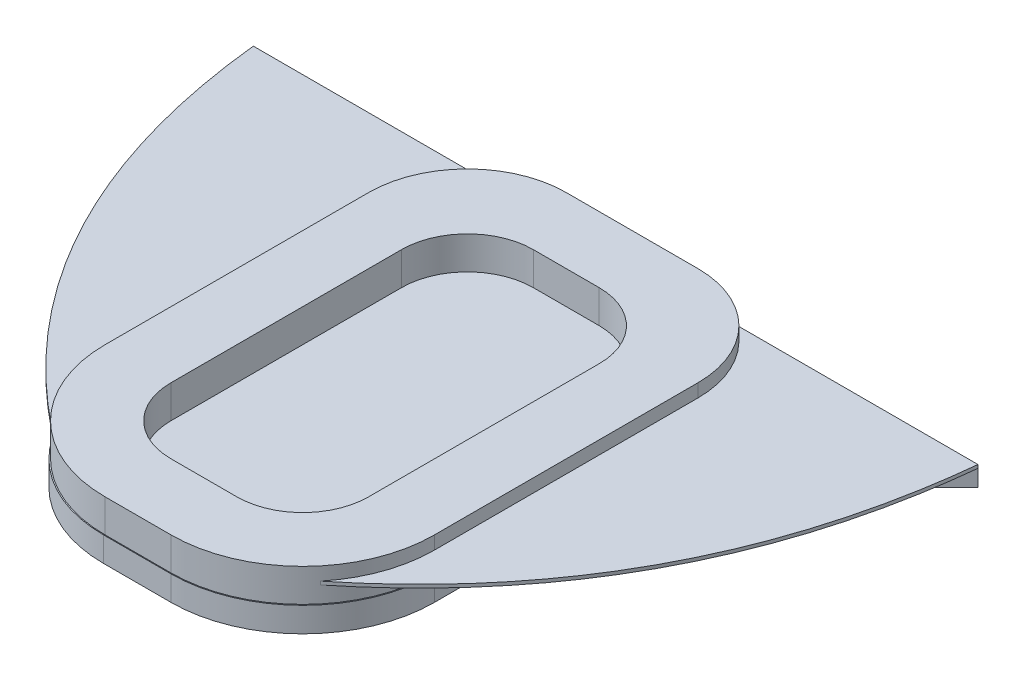
SolidWorks part; units mm, degrees
ref_plane "前视基准面" through (0, 0, 0) normal (0, 0, 1) x (1, 0, 0)
ref_plane "上视基准面" through (0, 0, 0) normal (0, 1, 0) x (1, 0, 0)
ref_plane "右视基准面" through (0, 0, 0) normal (1, 0, 0) x (0, 0, -1)
sketch "草图1" plane through (0, 0, 0) normal (0, 1, 0) x (1, 0, 0)
  line L1 (-4.05, 15.05) -> (4.05, 15.05)
  line L2 (-10.05, 9.05) -> (-10.05, -7.05)
  line L3 (-2.05, -15.05) -> (2.05, -15.05)
  line L4 (10.05, 9.05) -> (10.05, -7.05)
  line L5 (-10.05, 15.05) -> (10.05, -15.05) construction
  line L6 (-10.05, -15.05) -> (10.05, 15.05) construction
  arc A0 (-4.05, 15.05) -> (-10.05, 9.05) centre (-4.05, 9.05) ccw
  arc A1 (4.05, 15.05) -> (10.05, 9.05) centre (4.05, 9.05) cw
  arc A2 (2.05, -15.05) -> (10.05, -7.05) centre (2.05, -7.05) ccw
  arc A3 (-10.05, -7.05) -> (-2.05, -15.05) centre (-2.05, -7.05) ccw
  point P0 (0, 0)
  dimension "D3" = 6
  dimension "D4" = 8
  dimension "D1" = 20.1
  dimension "D2" = 30.1
extrude "凸台-拉伸1" add sketch "草图1" along normal blind 1.5
sketch "草图2" plane through (0, 1.5, 0) normal (0, 1, 0) x (1, 0, 0)
  line L0 (-7, -10) -> (-7, -13)
  line L1 (-2, 12) -> (-20, 12)
  line L2 (-2, 12) -> (-2, 14)
  line L3 (-2, 14) -> (-20, 14)
  line L4 (-20, 12) -> (-20, 14)
  line L5 (-7, 12) -> (-9, 12)
  line L6 (-7, 12) -> (-7, -10)
  line L7 (-7, -10) -> (-9, -10)
  line L8 (-9, 12) -> (-9, -10)
  line L9 (-7, -13) -> (-9, -10)
  line L10 (-20, 14) -> (-22, 14)
  line L11 (-22, 14) -> (-20, 12)
  line L12 (0, 0) -> (0, 16.1646) construction
  line L13 (20, 14) -> (22, 14)
  line L14 (22, 14) -> (20, 12)
  line L15 (7, -10) -> (7, -13)
  line L16 (7, -13) -> (9, -10)
  line L17 (7, -10) -> (9, -10)
  line L18 (9, 12) -> (9, -10)
  line L19 (7, 12) -> (9, 12)
  line L20 (7, 12) -> (7, -10)
  line L21 (2, 14) -> (20, 14)
  line L22 (20, 12) -> (20, 14)
  line L23 (2, 12) -> (20, 12)
  line L24 (2, 12) -> (2, 14)
  point P4 (-7, -13)
  point P11 (-22, 14)
  arc M9 (-4.05, 15.05) -> (-10.05, 9.05) centre (-4.05, 9.05) ccw
  arc M15 (10.05, 9.05) -> (4.05, 15.05) centre (4.05, 9.05) ccw
  dimension "D1" = 2
  dimension "D2" = 18
  dimension "D3" = 2
  dimension "D4" = 22
extrude "凸台-拉伸2" add sketch "草图2" along normal blind 1 contours L1 L8 L7 L6 | L2 L3 L1 M9 | L4 L1 L3 M9 | L10 L11 L4 | L9 L0 L7 | L24 L23 L19 L21 M15 | L23 L22 L21 M15 | L22 L14 L13 | L19 L20 L17 L18 | L17 L15 L16
sketch "草图3" plane through (0, 2.5, 0) normal (0, 1, 0) x (1, 0, 0)
  line L0 (-7, -13) -> (-7, 14)
  line L1 (-2, 14) -> (-7.4408, 14) construction
  line L2 (0, 0) -> (0, 19.1475) construction
  line L3 (7, -13) -> (7, 14)
  line L4 (-22, 14) -> (-7, 14)
  line L5 (22, 14) -> (7, 14)
  spline S0 degree 2 poles (-22, 14) (-20.2033, -3.1492) (-7, -13) knots 0 0 0 1 1 1
  spline S1 degree 2 poles (22, 14) (20.2033, -3.1492) (7, -13) knots 0 0 0 1 1 1
extrude "凸台-拉伸3" add sketch "草图3" along normal blind 0.2
sketch "草图4" plane through (0, 1.5, 0) normal (0, 1, 0) x (1, 0, 0)
  line L1 (-4, 15) -> (4, 15)
  line L2 (-10, 9) -> (-10, -7)
  line L3 (-2, -15) -> (2, -15)
  line L4 (10, 9) -> (10, -7)
  line L5 (-10, 15) -> (10, -15) construction
  line L6 (-10, -15) -> (10, 15) construction
  line L7 (-2, 11) -> (2, 11)
  line L8 (-6, 7) -> (-6, -7)
  line L9 (-2, -11) -> (2, -11)
  line L10 (6, 7) -> (6, -7)
  line L11 (-6, 11) -> (6, -11) construction
  line L12 (-6, -11) -> (6, 11) construction
  arc A0 (-4, 15) -> (-10, 9) centre (-4, 9) ccw
  arc A1 (4, 15) -> (10, 9) centre (4, 9) cw
  arc A2 (2, -15) -> (10, -7) centre (2, -7) ccw
  arc A3 (-10, -7) -> (-2, -15) centre (-2, -7) ccw
  arc A4 (-2, 11) -> (-6, 7) centre (-2, 7) ccw
  arc A5 (2, 11) -> (6, 7) centre (2, 7) cw
  arc A6 (2, -11) -> (6, -7) centre (2, -7) ccw
  arc A7 (-6, -7) -> (-2, -11) centre (-2, -7) ccw
  point P0 (0, 0)
  point P18 (0, 0)
  dimension "D3" = 6
  dimension "D4" = 8
  dimension "D7" = 4
  dimension "D1" = 20
  dimension "D2" = 30
  dimension "D5" = 12
  dimension "D6" = 22
extrude "凸台-拉伸4" add sketch "草图4" along normal blind 2
